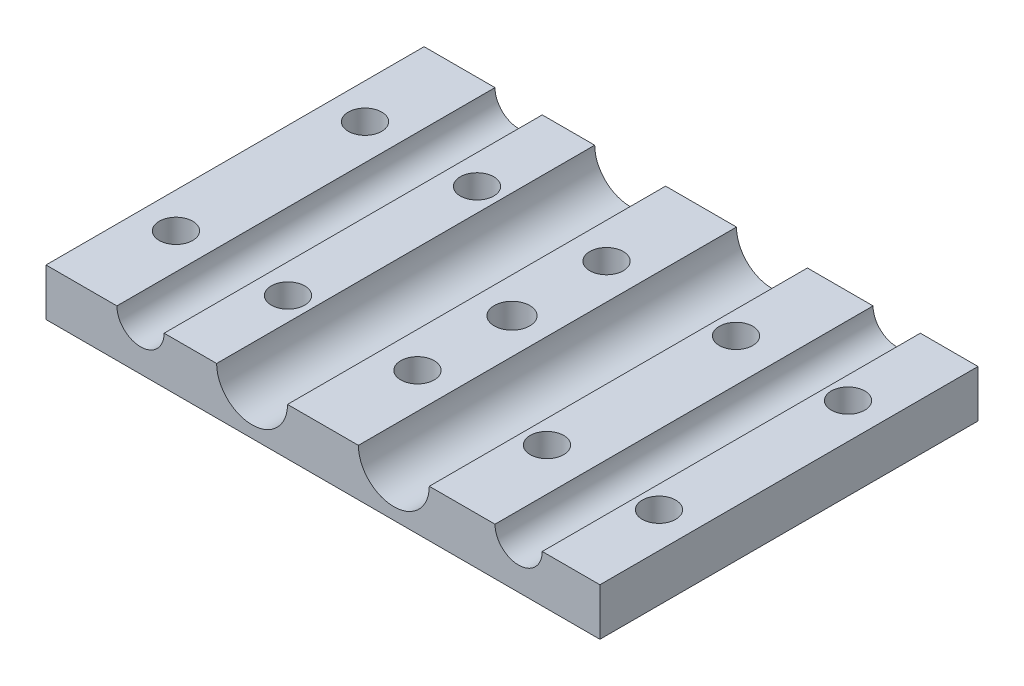
SolidWorks part; units mm, degrees
material "Copper"
ref_plane "Front Plane" through (0, 0, 0) normal (0, 0, 1) x (1, 0, 0)
ref_plane "Top Plane" through (0, 0, 0) normal (0, 1, 0) x (1, 0, 0)
ref_plane "Right Plane" through (0, 0, 0) normal (1, 0, 0) x (0, 0, -1)
sketch "Sketch1" plane through (0, 0, 0) normal (0, 1, 0) x (1, 0, 0)
  line L1 (-37.211, 25.4) -> (37.211, 25.4)
  line L2 (-37.211, 25.4) -> (-37.211, -25.4)
  line L3 (-37.211, -25.4) -> (37.211, -25.4)
  line L4 (37.211, 25.4) -> (37.211, -25.4)
  dimension "D1" = 50.8
  dimension "D2" = 74.422
  dimension "D3" = 37.211
  dimension "D4" = 25.4
extrude "Boss-Extrude1" add sketch "Sketch1" along normal blind 6.35
sketch "Sketch2" plane through (0, 0, 25.4) normal (0, 0, 1) x (1, 0, 0)
  line L0 (-37.211, 0) -> (37.211, 0) construction
  line L1 (-37.211, 6.35) -> (-37.211, 0) construction
  circle A0 centre (-24.511, 0) radius 3.175
  circle A1 centre (26.289, 0) radius 3.175
  dimension "D3" = 6.35
  dimension "D1" = 50.8
  dimension "D2" = 12.7
extrude "Cut-Extrude1" cut sketch "Sketch2" against normal through all
sketch "Sketch3" plane through (0, 0, 25.4) normal (0, 0, 1) x (1, 0, 0)
  line L0 (-21.336, 0) -> (23.114, 0) construction
  circle A0 centre (-9.525, 0) radius 4.7625
  circle A1 centre (9.525, 0) radius 4.7625
  dimension "D1" = 9.525
  dimension "D2" = 19.05
  dimension "D3" = 9.525
extrude "Cut-Extrude2" cut sketch "Sketch3" against normal through all
hole_wizard "#8 Clearance Hole1" positions "Sketch5" profile "Sketch4" hole size "#8" standard "ANSI Inch" end condition through all
sketch "Sketch5" plane through (0, 6.35, 0) normal (0, 1, 0) x (1, 0, 0)
  line L2 (37.211, 25.4) -> (-37.211, 25.4) construction
  line L3 (-37.211, -25.4) -> (37.211, -25.4) construction
  line L4 (-37.211, 25.4) -> (-37.211, -25.4) construction
  line L5 (37.211, -25.4) -> (37.211, 25.4) construction
  point P0 (-32.4485, 12.7)
  point P2 (-32.4485, -12.7)
  point P4 (-17.399, -12.7)
  point P6 (0, -12.7)
  point P8 (17.399, -12.7)
  point P10 (32.4485, -12.7)
  point P12 (32.4485, 12.7)
  point P14 (17.399, 12.7)
  point P16 (0, 12.7)
  point P18 (-17.399, 12.7)
  dimension "D1" = 12.7
  dimension "D2" = 12.7
  dimension "D3" = 4.7625
  dimension "D4" = 4.7625
  dimension "D5" = 19.812
  dimension "D6" = 19.812
sketch "Sketch4" plane through (-32.4485, 6.35, -12.7) normal (1, 0, 0) x (0, 0, 1)
  line L0 (0, 0) -> (0, 6.35)
  line L1 (0, 6.35) -> (2.2479, 6.35)
  line L2 (2.2479, 6.35) -> (2.2479, 0)
  line L5 (2.2479, 0) -> (0, 0)
  line L11 (0, -6.35) -> (0, 107.95) construction
  dimension "Thru Hole Dia." = 4.4958
  dimension "Thru Hole Depth" = 6.35
sketch "Sketch6" plane through (0, 6.35, 0) normal (0, 1, 0) x (1, 0, 0)
  line L0 (-17.399, 17.018) -> (-17.399, 8.382) construction
  line L1 (-13.081, 17.018) -> (-13.081, 8.382)
  line L2 (-21.717, 17.018) -> (-21.717, 8.382)
  line L3 (0, 25.4) -> (0, 0) construction
  line L4 (37.211, 25.4) -> (-37.211, 25.4) construction
  line L5 (37.211, 0) -> (0, 0) construction
  line L6 (37.211, -25.4) -> (37.211, 25.4) construction
  line L7 (17.399, 17.018) -> (17.399, 8.382) construction
  line L8 (13.081, 17.018) -> (13.081, 8.382)
  line L9 (21.717, 17.018) -> (21.717, 8.382)
  line L10 (17.399, -17.018) -> (17.399, -8.382) construction
  line L11 (13.081, -17.018) -> (13.081, -8.382)
  line L12 (21.717, -17.018) -> (21.717, -8.382)
  line L13 (-17.399, -17.018) -> (-17.399, -8.382) construction
  line L14 (-13.081, -17.018) -> (-13.081, -8.382)
  line L15 (-21.717, -17.018) -> (-21.717, -8.382)
  line L16 (0, 17.018) -> (0, 8.382) construction
  line L17 (4.318, 17.018) -> (4.318, 8.382)
  line L18 (-4.318, 17.018) -> (-4.318, 8.382)
  line L19 (0, -17.018) -> (0, -8.382) construction
  line L20 (4.318, -17.018) -> (4.318, -8.382)
  line L21 (-4.318, -17.018) -> (-4.318, -8.382)
  line L22 (-32.4485, 17.018) -> (-32.4485, 8.382) construction
  line L23 (-28.1305, 17.018) -> (-28.1305, 8.382)
  line L24 (-36.7665, 17.018) -> (-36.7665, 8.382)
  line L25 (-32.4485, -17.018) -> (-32.4485, -8.382) construction
  line L26 (-28.1305, -17.018) -> (-28.1305, -8.382)
  line L27 (-36.7665, -17.018) -> (-36.7665, -8.382)
  line L28 (32.4485, 17.018) -> (32.4485, 8.382) construction
  line L29 (28.1305, 17.018) -> (28.1305, 8.382)
  line L30 (36.7665, 17.018) -> (36.7665, 8.382)
  line L31 (32.4485, -17.018) -> (32.4485, -8.382) construction
  line L32 (28.1305, -17.018) -> (28.1305, -8.382)
  line L33 (36.7665, -17.018) -> (36.7665, -8.382)
  arc A0 (-13.081, 17.018) -> (-21.717, 17.018) centre (-17.399, 17.018) ccw
  arc A1 (-21.717, 8.382) -> (-13.081, 8.382) centre (-17.399, 8.382) ccw
  arc A2 (13.081, 17.018) -> (21.717, 17.018) centre (17.399, 17.018) cw
  arc A3 (21.717, 8.382) -> (13.081, 8.382) centre (17.399, 8.382) cw
  arc A4 (13.081, -17.018) -> (21.717, -17.018) centre (17.399, -17.018) ccw
  arc A5 (21.717, -8.382) -> (13.081, -8.382) centre (17.399, -8.382) ccw
  arc A6 (-13.081, -17.018) -> (-21.717, -17.018) centre (-17.399, -17.018) cw
  arc A7 (-21.717, -8.382) -> (-13.081, -8.382) centre (-17.399, -8.382) cw
  arc A11 (4.318, 17.018) -> (-4.318, 17.018) centre (0, 17.018) ccw
  arc A12 (-4.318, 8.382) -> (4.318, 8.382) centre (0, 8.382) ccw
  arc A13 (4.318, -17.018) -> (-4.318, -17.018) centre (0, -17.018) cw
  arc A14 (-4.318, -8.382) -> (4.318, -8.382) centre (0, -8.382) cw
  arc A15 (-28.1305, 17.018) -> (-36.7665, 17.018) centre (-32.4485, 17.018) ccw
  arc A16 (-36.7665, 8.382) -> (-28.1305, 8.382) centre (-32.4485, 8.382) ccw
  arc A17 (-28.1305, -17.018) -> (-36.7665, -17.018) centre (-32.4485, -17.018) cw
  arc A18 (-36.7665, -8.382) -> (-28.1305, -8.382) centre (-32.4485, -8.382) cw
  arc A19 (28.1305, 17.018) -> (36.7665, 17.018) centre (32.4485, 17.018) cw
  arc A20 (36.7665, 8.382) -> (28.1305, 8.382) centre (32.4485, 8.382) cw
  arc A21 (28.1305, -17.018) -> (36.7665, -17.018) centre (32.4485, -17.018) ccw
  arc A22 (36.7665, -8.382) -> (28.1305, -8.382) centre (32.4485, -8.382) ccw
  point P3 (-17.399, 12.7)
  point P18 (17.399, 12.7)
  point P25 (17.399, -12.7)
  point P32 (-17.399, -12.7)
  point P39 (0, 12.7)
  point P46 (0, -12.7)
  point P54 (-32.4485, 12.7)
  point P61 (-32.4485, -12.7)
  point P68 (32.4485, 12.7)
  point P75 (32.4485, -12.7)
  dimension "D1" = 8.636
  dimension "D2" = 12.7
  dimension "D3" = 8.636
  dimension "D4" = 12.7
  dimension "D5" = 8.636
  dimension "D6" = 8.636
  dimension "D7" = 12.7
  dimension "D8" = 8.636
  dimension "D9" = 8.636
extrude "Cut-Extrude3" cut sketch "Sketch6" against normal blind 3.175
sketch "Sketch7" plane through (0, 6.35, 0) normal (0, 1, 0) x (1, 0, 0)
  circle A0 centre (0, 0) radius 2.3813
  dimension "D1" = 4.7625
extrude "Cut-Extrude4" cut sketch "Sketch7" against normal through all
sketch "Sketch8" plane through (0, 0, 25.4) normal (0, 0, 1) x (1, 0, 0)
  line L0 (-4.7625, 0) -> (4.7625, 0) construction
  circle A0 centre (0, 1.5875) radius 0.8509
  dimension "D2" = 1.7018
  dimension "D1" = 1.5875
extrude "Cut-Extrude5" cut sketch "Sketch8" against normal blind 9.525
move or copy body "Body-Move/Copy1" bodies to move or copy 112 copy no rotation origin (0, 3.175, 0) rotation axis (1, 0, 0) rotation angle 180
